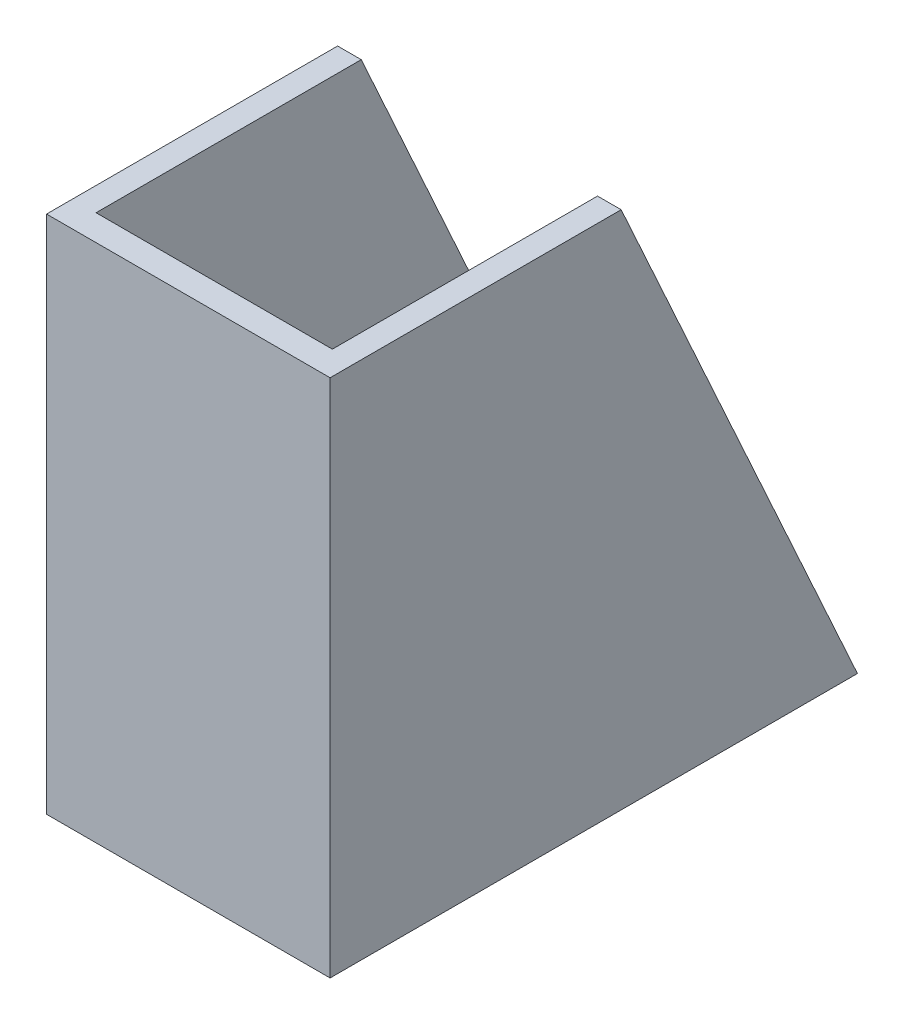
SolidWorks part; units mm, degrees
ref_plane "Front Plane" through (0, 0, 0) normal (0, 0, 1) x (1, 0, 0)
ref_plane "Top Plane" through (0, 0, 0) normal (0, 1, 0) x (1, 0, 0)
ref_plane "Right Plane" through (0, 0, 0) normal (1, 0, 0) x (0, 0, -1)
sketch "Sketch1" plane through (0, 0, 0) normal (1, 0, 0) x (0, 0, -1)
  line L0 (30.795, 76.2699) -> (80.795, -33.7301)
  line L1 (30.795, 76.2699) -> (-30.795, 76.2699)
  line L3 (80.795, -33.7301) -> (-30.795, -33.7301)
  line L4 (-30.795, 76.2699) -> (-30.795, -33.7301)
  point P0 (0, 0)
  dimension "D1" = 61.59
  dimension "D2" = 110
  dimension "D3" = 111.59
extrude "Boss-Extrude1" add sketch "Sketch1" against normal blind 60
ref_plane "Plane1" through (-30, 0, 0) normal (1, 0, 0) x (0, 0, -1)
sketch "Sketch2" plane through (-30, 0, 0) normal (1, 0, 0) x (0, 0, -1)
  line L1 (30.795, 76.2699) -> (-25.315, 76.2699)
  line L2 (30.795, 76.2699) -> (-30.795, 76.2699) construction
  line L3 (-25.315, 76.2699) -> (-25.315, 71.2699)
  line L4 (-25.315, 71.2699) -> (-25.795, 71.2699)
  line L5 (-25.795, 71.2699) -> (-25.795, -28.7301)
  line L6 (-25.795, -28.7301) -> (78.5223, -28.7301)
  line L7 (80.795, -33.7301) -> (30.795, 76.2699) construction
  line L8 (78.5223, -28.7301) -> (30.795, 76.2699)
extrude "Cut-Extrude1" cut sketch "Sketch2" against normal blind 25 and the other way blind 25
